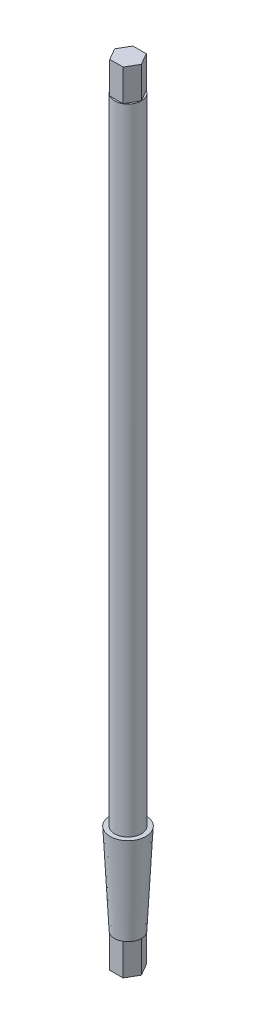
SolidWorks part; units mm, degrees
material "PVC 0.007 Plasticized"
ref_plane "Front Plane" through (0, 0, 0) normal (0, 0, 1) x (1, 0, 0)
ref_plane "Top Plane" through (0, 0, 0) normal (0, 1, 0) x (1, 0, 0)
ref_plane "Right Plane" through (0, 0, 0) normal (1, 0, 0) x (0, 0, -1)
sketch "Sketch1" plane through (0, 0, 0) normal (0, 1, 0) x (1, 0, 0)
  line L1 (1.475, -2.5548) -> (2.95, 0)
  line L2 (2.95, 0) -> (1.475, 2.5548)
  line L3 (1.475, 2.5548) -> (-1.475, 2.5548)
  line L4 (-1.475, 2.5548) -> (-2.95, 0)
  line L5 (-2.95, 0) -> (-1.475, -2.5548)
  line L6 (-1.475, -2.5548) -> (1.475, -2.5548)
  circle A0 centre (0, 0) radius 2.5548 construction
  dimension "D1" = 5.9
extrude "Boss-Extrude1" add sketch "Sketch1" along normal blind 7
sketch "Sketch2" plane through (0, 7, 0) normal (0, 1, 0) x (1, 0, 0)
  circle A0 centre (0, 0) radius 2.95
extrude "Boss-Extrude2" add sketch "Sketch2" along normal blind 160
ref_plane "Plane1" through (0, 27, 0) normal (0, -1, 0) x (-1, 0, 0)
sketch "Sketch4" plane through (0, 27, 0) normal (0, -1, 0) x (-1, 0, 0)
  circle A0 centre (0, 0) radius 3.95
  arc A1 (1.475, -2.5548) -> (2.95, 0) centre (0, 0) ccw construction
  dimension "D1" = 1
sketch "Sketch5" plane through (0, 7, 0) normal (0, -1, 0) x (1, 0, 0)
  circle A0 centre (0, 0) radius 2.95
  arc A1 (-1.475, 2.5548) -> (-2.95, 0) centre (0, 0) ccw construction
loft "Loft1" add profiles "Sketch5", "Sketch4"
sketch "Sketch6" plane through (0, 167, 0) normal (0, 1, 0) x (1, 0, 0)
  line L1 (1.475, -2.5548) -> (2.95, 0)
  line L2 (2.95, 0) -> (1.475, 2.5548)
  line L3 (1.475, 2.5548) -> (-1.475, 2.5548)
  line L4 (-1.475, 2.5548) -> (-2.95, 0)
  line L5 (-2.95, 0) -> (-1.475, -2.5548)
  line L6 (-1.475, -2.5548) -> (1.475, -2.5548)
  circle A0 centre (0, 0) radius 2.5548 construction
  circle A1 centre (0, 0) radius 2.95 construction
extrude "Boss-Extrude3" add sketch "Sketch6" along normal blind 7
